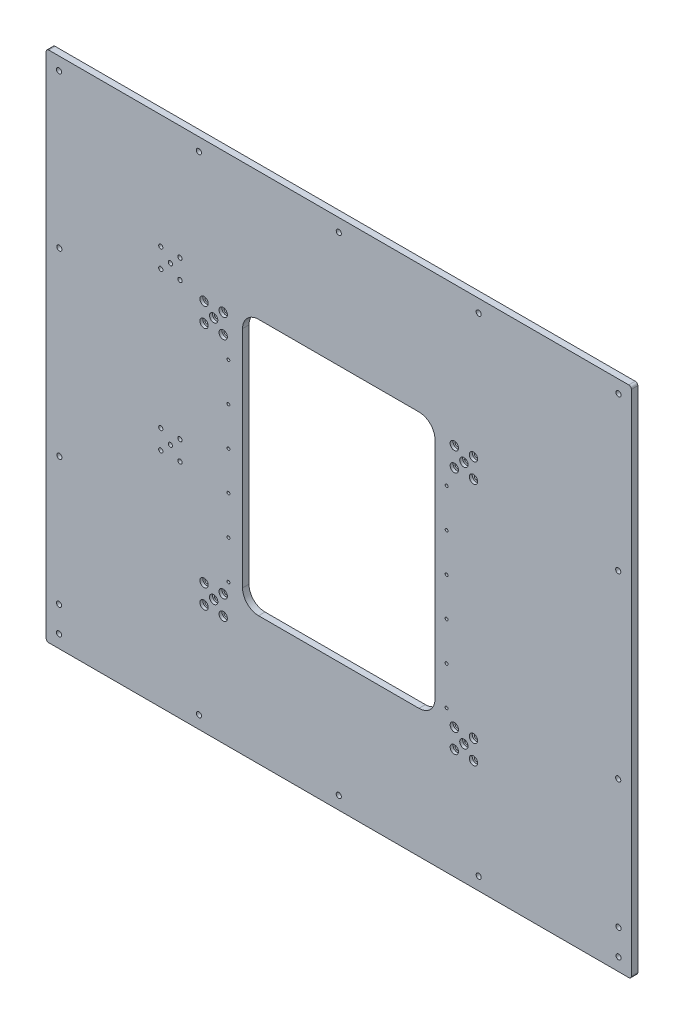
SolidWorks part; units mm, degrees
ref_plane "Plan de face" through (0, 0, 0) normal (0, 0, 1) x (1, 0, 0)
ref_plane "Plan de dessus" through (0, 0, 0) normal (0, 1, 0) x (1, 0, 0)
ref_plane "Plan de droite" through (0, 0, 0) normal (1, 0, 0) x (0, 0, -1)
sketch "Esquisse1" plane through (0, 0, 0) normal (0, 0, 1) x (1, 0, 0)
  line L1 (-452, -400) -> (452, -400)
  line L2 (-456, -396) -> (-456, 396)
  line L3 (-452, 400) -> (452, 400)
  line L4 (456, -396) -> (456, 396)
  line L5 (-456, -400) -> (456, 400) construction
  line L6 (-456, 400) -> (456, -400) construction
  line L7 (0, 400) -> (0, -400) construction
  line L8 (-456, 0) -> (456, 0) construction
  arc A0 (-456, 396) -> (-452, 400) centre (-452, 396) cw
  arc A1 (456, 396) -> (452, 400) centre (452, 396) ccw
  arc A2 (452, -400) -> (456, -396) centre (452, -396) ccw
  arc A3 (-456, -396) -> (-452, -400) centre (-452, -396) ccw
  circle A4 centre (436, 380) radius 4
  circle A5 centre (435.5, -140) radius 4
  circle A6 centre (435.5, 141) radius 4
  circle A7 centre (-435.5, -140) radius 4
  circle A8 centre (-436, 380) radius 4
  circle A9 centre (-435.5, 141) radius 4
  circle A10 centre (436, -380) radius 4
  circle A11 centre (436, -340) radius 4
  circle A12 centre (-436, -340) radius 4
  circle A13 centre (-436, -380) radius 4
  circle A14 centre (218, -380) radius 4
  circle A15 centre (0, -380) radius 4
  circle A16 centre (-218, -380) radius 4
  circle A17 centre (-218, 380) radius 4
  circle A18 centre (0, 380) radius 4
  circle A19 centre (218, 380) radius 4
  point P0 (0, 0)
  dimension "D3" = 4
  dimension "D4" = 4
  dimension "D5" = 4
  dimension "D6" = 4
  dimension "D7" = 8
  dimension "D8" = 20
  dimension "D9" = 20
  dimension "D11" = 20.5
  dimension "D12" = 259
  dimension "D13" = 8
  dimension "D14" = 2
  dimension "D1" = 912
  dimension "D2" = 800
  dimension "D15" = 4
  dimension "D10" = 2
extrude "Boss.-Extru.1" add sketch "Esquisse1" along normal blind 10
sketch "Esquisse2" plane through (0, 0, 10) normal (0, 0, 1) x (1, 0, 0)
  line L0 (-125, -200) -> (125, -200)
  line L1 (-150, -175) -> (-150, 175)
  line L2 (150, -175) -> (150, 175)
  line L3 (-125, 200) -> (125, 200)
  line L4 (-125, -175) -> (125, 175) construction
  arc A0 (-125, 200) -> (-150, 175) centre (-125, 175) ccw
  arc A1 (125, 200) -> (150, 175) centre (125, 175) cw
  arc A2 (150, -175) -> (125, -200) centre (125, -175) cw
  arc A3 (-150, -175) -> (-125, -200) centre (-125, -175) ccw
  point P9 (150, 200)
  point P12 (150, -200)
  dimension "D3" = 300
  dimension "D2" = 25
  dimension "D1" = 400
extrude "Enlèv. mat.-Extru.1" cut sketch "Esquisse2" against normal through all
hole_wizard "Dégagement M61" [suppressed] positions "Esquisse4" profile "Esquisse3" hole size "M6" standard "JIS"
sketch "Esquisse4" plane through (0, 0, 10) normal (0, 0, 1) x (1, 0, 0)
  point P0 (-277.4372, 232)
  point P2 (-247.5898, 232)
  point P4 (-247.5898, 201.8404)
  point P6 (-277.6003, 201.8404)
  point P8 (-262.5, 217)
sketch "Esquisse3" plane through (-277.4372, 232, 10) normal (1, 0, 0) x (0, -1, 0)
  line L0 (0, 0) -> (0, 10)
  line L1 (0, 10) -> (3.3, 10)
  line L2 (3.3, 10) -> (3.3, 0)
  line L5 (3.3, 0) -> (0, 0)
  line L11 (0, -6.35) -> (0, 107.95) construction
  dimension "Diamètre du perçage jusqu'au prochain" = 6.6
  dimension "Profondeur du perçage jusqu'au prochain" = 10
pattern_linear "Répétition linéaire1" [suppressed] count 2 spacing 245
hole_wizard "Chambrage pour vis à tête ronde bombée M61" [suppressed] positions "Esquisse6" profile "Esquisse5" counterbore size "M6" standard "Ansi Metric"
sketch "Esquisse6" plane through (0, 0, 0) normal (0, 0, -1) x (-1, 0, 0)
  point P0 (247.5898, 232)
  point P2 (277.4372, 232)
  point P4 (277.6003, 201.8404)
  point P6 (247.5898, 201.8404)
  point P8 (262.5, 217)
  point P10 (247.5898, -13)
  point P12 (277.4372, -13)
  point P14 (262.5, -28)
sketch "Esquisse5" plane through (-247.5898, 232, 0) normal (1, 0, 0) x (0, 1, 0)
  line L0 (0, 0) -> (0, 10)
  line L1 (0, 10) -> (3.3, 10)
  line L2 (3.3, 4.625) -> (3.3, 10)
  line L3 (3.3, 4.625) -> (3.325, 4.6)
  line L4 (3.325, 4.6) -> (6.5, 4.6)
  line L5 (6.5, 4.6) -> (6.5, 0)
  line L7 (0, 0) -> (6.5, 0)
  line L9 (-3.3, 4.625) -> (-3.325, 4.6) construction
  line L11 (0, -6.35) -> (0, 107.95) construction
  dimension "Diamètre du perçage jusqu'au prochain" = 6.6
  dimension "Profondeur du perçage jusqu'au prochain" = 10
  dimension "Diamètre du chambrage" = 13
  dimension "Profondeur du chambrage" = 4.6
  dimension "Diamètre du fraisage milieu" = 6.65
  dimension "Angle du fraisage milieu" = 90
hole_wizard "Chambrage pour vis à tête ronde bombée M62" [suppressed] positions "Esquisse8" profile "Esquisse7" counterbore size "M6" standard "Ansi Metric"
sketch "Esquisse8" plane through (0, 0, 0) normal (0, 0, -1) x (-1, 0, 0)
  point P0 (247.5898, -43.1596)
  point P2 (277.6003, -43.1596)
sketch "Esquisse7" plane through (-247.5898, -43.1596, 0) normal (1, 0, 0) x (0, 1, 0)
  line L0 (0, 0) -> (0, 10)
  line L1 (0, 10) -> (3.3, 10)
  line L2 (3.3, 4.625) -> (3.3, 10)
  line L3 (3.3, 4.625) -> (3.325, 4.6)
  line L4 (3.325, 4.6) -> (6.5, 4.6)
  line L5 (6.5, 4.6) -> (6.5, 0)
  line L7 (0, 0) -> (6.5, 0)
  line L9 (-3.3, 4.625) -> (-3.325, 4.6) construction
  line L11 (0, -6.35) -> (0, 107.95) construction
  dimension "Diamètre du perçage jusqu'au prochain" = 6.6
  dimension "Profondeur du perçage jusqu'au prochain" = 10
  dimension "Diamètre du chambrage" = 13
  dimension "Profondeur du chambrage" = 4.6
  dimension "Diamètre du fraisage milieu" = 6.65
  dimension "Angle du fraisage milieu" = 90
hole_wizard "Dégagement M62" [suppressed] positions "Esquisse10" profile "Esquisse9" hole size "M6" standard "JIS"
sketch "Esquisse10" plane through (0, 0, 0) normal (0, 0, -1) x (-1, 0, 0)
  point P0 (-209.6182, 209)
  point P2 (-180.0241, 209)
  point P4 (-180.0241, 179.1391)
  point P6 (-209.6182, 179)
  point P8 (-195, 194)
sketch "Esquisse9" plane through (209.6182, 209, 0) normal (1, 0, 0) x (0, 1, 0)
  line L0 (0, 0) -> (0, 10)
  line L1 (0, 10) -> (3.3, 10)
  line L2 (3.3, 10) -> (3.3, 0)
  line L5 (3.3, 0) -> (0, 0)
  line L11 (0, -6.35) -> (0, 107.95) construction
  dimension "Diamètre du perçage jusqu'au prochain" = 6.6
  dimension "Profondeur du perçage jusqu'au prochain" = 10
pattern_linear "Répétition linéaire2" [suppressed] count 2 spacing 390 count 2 spacing 380
hole_wizard "Chambrage pour vis à tête ronde bombée M63" [suppressed] positions "Esquisse14" profile "Esquisse13" counterbore size "M6" standard "Ansi Metric"
sketch "Esquisse14" plane through (0, 0, 10) normal (0, 0, 1) x (1, 0, 0)
  point P0 (-209.9759, 209)
  point P2 (-180.3818, 209)
  point P4 (-180.3818, 179)
  point P6 (-209.9759, 179)
  point P8 (-195, 194)
sketch "Esquisse13" plane through (-209.9759, 209, 10) normal (1, 0, 0) x (0, -1, 0)
  line L0 (0, 0) -> (0, 10)
  line L1 (0, 10) -> (3.3, 10)
  line L2 (3.3, 4.625) -> (3.3, 10)
  line L3 (3.3, 4.625) -> (3.325, 4.6)
  line L4 (3.325, 4.6) -> (6.5, 4.6)
  line L5 (6.5, 4.6) -> (6.5, 0)
  line L7 (0, 0) -> (6.5, 0)
  line L9 (-3.3, 4.625) -> (-3.325, 4.6) construction
  line L11 (0, -6.35) -> (0, 107.95) construction
  dimension "Diamètre du perçage jusqu'au prochain" = 6.6
  dimension "Profondeur du perçage jusqu'au prochain" = 10
  dimension "Diamètre du chambrage" = 13
  dimension "Profondeur du chambrage" = 4.6
  dimension "Diamètre du fraisage milieu" = 6.65
  dimension "Angle du fraisage milieu" = 90
pattern_linear "Répétition linéaire3" [suppressed] count 2 spacing 390 count 2 spacing 380
pattern_linear "Répétition linéaire4" [suppressed] count 2 spacing 27
hole_wizard "Dégagement M63" positions "Esquisse16" profile "Esquisse15" hole size "M6" standard "JIS" end condition through all
sketch "Esquisse16" plane through (0, 0, 10) normal (0, 0, 1) x (1, 0, 0)
  point P0 (-247.5, 222.1335)
  point P2 (-277.4031, 222.0438)
  point P4 (-262.5, 207)
  point P6 (-277.4031, 191.9292)
  point P8 (-247.5, 191.9292)
sketch "Esquisse15" plane through (-247.5, 222.1335, 10) normal (1, 0, 0) x (0, -1, 0)
  line L0 (0, 0) -> (0, 10)
  line L1 (0, 10) -> (3.3, 10)
  line L2 (3.3, 10) -> (3.3, 0)
  line L5 (3.3, 0) -> (0, 0)
  line L11 (0, -6.35) -> (0, 107.95) construction
  dimension "Diamètre du perçage jusqu'au prochain" = 6.6
  dimension "Profondeur du perçage jusqu'au prochain" = 10
hole_wizard "Chambrage pour vis à tête ronde bombée M64" positions "Esquisse18" profile "Esquisse17" counterbore size "M6" standard "Ansi Metric" end condition through all
sketch "Esquisse18" plane through (0, 0, 0) normal (0, 0, -1) x (-1, 0, 0)
  point P0 (247.5, 222.1335)
  point P2 (277.4031, 222.0438)
  point P4 (277.4031, 191.9292)
  point P6 (247.5, 191.9292)
  point P9 (262.5, 207)
sketch "Esquisse17" plane through (-247.5, 222.1335, 0) normal (1, 0, 0) x (0, 1, 0)
  line L0 (0, 0) -> (0, 10)
  line L1 (0, 10) -> (3.3, 10)
  line L2 (3.3, 4.625) -> (3.3, 10)
  line L3 (3.3, 4.625) -> (3.325, 4.6)
  line L4 (3.325, 4.6) -> (6.5, 4.6)
  line L5 (6.5, 4.6) -> (6.5, 0)
  line L7 (0, 0) -> (6.5, 0)
  line L9 (-3.3, 4.625) -> (-3.325, 4.6) construction
  line L11 (0, -6.35) -> (0, 107.95) construction
  dimension "Diamètre du perçage jusqu'au prochain" = 6.6
  dimension "Profondeur du perçage jusqu'au prochain" = 10
  dimension "Diamètre du chambrage" = 13
  dimension "Profondeur du chambrage" = 4.6
  dimension "Diamètre du fraisage milieu" = 6.65
  dimension "Angle du fraisage milieu" = 90
pattern_linear "Répétition linéaire5" count 2 spacing 245 along (0, -1, 0) of "Chambrage pour vis à tête ronde bombée M64"
hole_wizard "Dégagement M64" positions "Esquisse20" profile "Esquisse19" hole size "M6" standard "JIS" end condition through all
sketch "Esquisse20" plane through (0, 0, 0) normal (0, 0, -1) x (-1, 0, 0)
  point P0 (195, 167)
  point P2 (209.9891, 182)
  point P4 (209.9891, 152.1079)
  point P6 (180.1229, 151.8122)
  point P8 (180.1229, 182)
sketch "Esquisse19" plane through (-195, 167, 0) normal (1, 0, 0) x (0, 1, 0)
  line L0 (0, 0) -> (0, 10)
  line L1 (0, 10) -> (3.3, 10)
  line L2 (3.3, 10) -> (3.3, 0)
  line L5 (3.3, 0) -> (0, 0)
  line L11 (0, -6.35) -> (0, 107.95) construction
  dimension "Diamètre du perçage jusqu'au prochain" = 6.6
  dimension "Profondeur du perçage jusqu'au prochain" = 10
hole_wizard "Chambrage pour vis à tête ronde bombée M65" positions "Esquisse22" profile "Esquisse21" counterbore size "M6" standard "Ansi Metric" end condition through all
sketch "Esquisse22" plane through (0, 0, 10) normal (0, 0, 1) x (1, 0, 0)
  point P0 (-209.9891, 182)
  point P2 (-180.1229, 182)
  point P4 (-209.9891, 152.1079)
  point P6 (-180.1229, 151.8122)
  point P7 (-195, 167)
sketch "Esquisse21" plane through (-209.9891, 182, 10) normal (1, 0, 0) x (0, -1, 0)
  line L0 (0, 0) -> (0, 10)
  line L1 (0, 10) -> (3.3, 10)
  line L2 (3.3, 4.625) -> (3.3, 10)
  line L3 (3.3, 4.625) -> (3.325, 4.6)
  line L4 (3.325, 4.6) -> (6.5, 4.6)
  line L5 (6.5, 4.6) -> (6.5, 0)
  line L7 (0, 0) -> (6.5, 0)
  line L9 (-3.3, 4.625) -> (-3.325, 4.6) construction
  line L11 (0, -6.35) -> (0, 107.95) construction
  dimension "Diamètre du perçage jusqu'au prochain" = 6.6
  dimension "Profondeur du perçage jusqu'au prochain" = 10
  dimension "Diamètre du chambrage" = 13
  dimension "Profondeur du chambrage" = 4.6
  dimension "Diamètre du fraisage milieu" = 6.65
  dimension "Angle du fraisage milieu" = 90
pattern_linear "Répétition linéaire6" count 2 spacing 380 along (0, -1, 0) count 2 spacing 390 along (1, 0, 0) of "Chambrage pour vis à tête ronde bombée M65"
hole_wizard "Dégagement M41" positions "Esquisse24" profile "Esquisse23" hole size "M4" standard "JIS" end condition through all
sketch "Esquisse24" plane through (0, 0, 10) normal (0, 0, 1) x (1, 0, 0)
  point P0 (-172, 122)
  point P2 (-172, 62)
  point P4 (-172, 2)
  point P6 (-172, -58)
  point P8 (-172, -118)
  point P10 (-172, -178)
  point P12 (168, -178)
  point P14 (168, -118)
  point P16 (168, -58)
  point P18 (168, 2)
  point P20 (168, 62)
  point P22 (168, 122)
sketch "Esquisse23" plane through (-172, 122, 10) normal (1, 0, 0) x (0, -1, 0)
  line L0 (0, 0) -> (0, 10)
  line L1 (0, 10) -> (2.25, 10)
  line L2 (2.25, 10) -> (2.25, 0)
  line L5 (2.25, 0) -> (0, 0)
  line L11 (0, -6.35) -> (0, 107.95) construction
  dimension "Diamètre du perçage jusqu'au prochain" = 4.5
  dimension "Profondeur du perçage jusqu'au prochain" = 10
